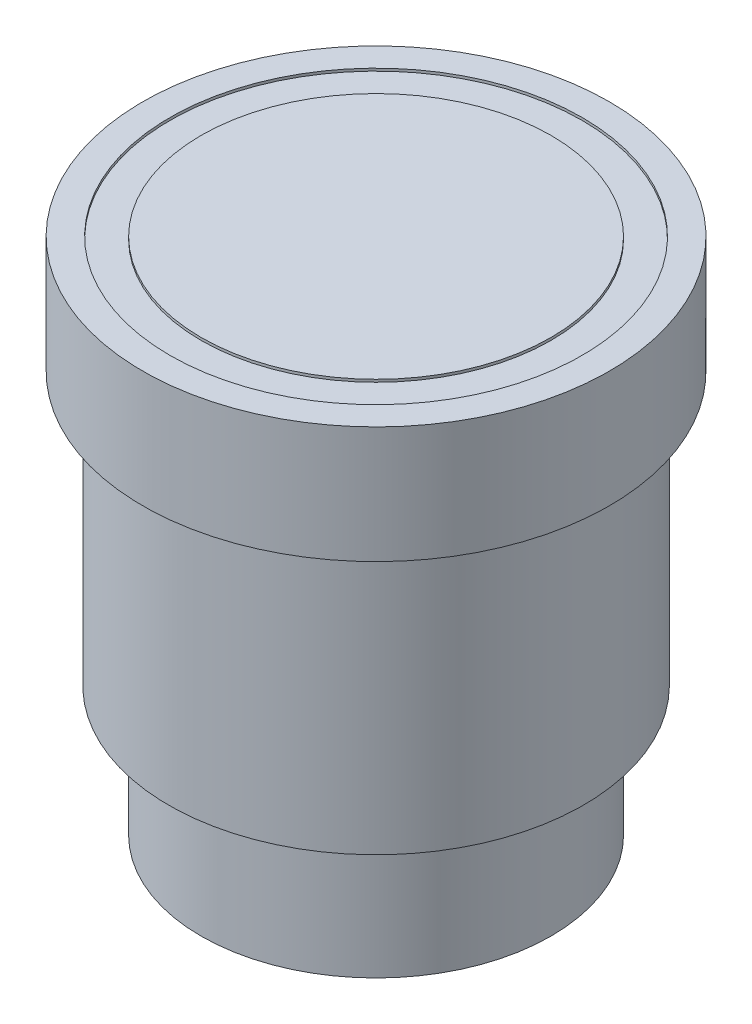
SolidWorks part; units mm, degrees
ref_plane "Front Plane" through (0, 0, 0) normal (0, 0, 1) x (1, 0, 0)
ref_plane "Top Plane" through (0, 0, 0) normal (0, 1, 0) x (1, 0, 0)
ref_plane "Right Plane" through (0, 0, 0) normal (1, 0, 0) x (0, 0, -1)
sketch "Sketch1" plane through (0, 0, 0) normal (1, 0, 0) x (0, 0, -1)
  line L0 (0, 0) -> (0, 50000) construction
  line L1 (0, 20) -> (9, 20)
  line L2 (9, 20) -> (9, 15.5)
  line L3 (9, 15.5) -> (8, 15.5)
  line L4 (8, 15.5) -> (8, 5)
  line L5 (8, 5) -> (6.75, 5)
  line L6 (6.75, 5) -> (6.75, 0)
  line L7 (6.75, 0) -> (0, 0)
  line L8 (0, 20) -> (0, 0)
  dimension "D1" = 20
  dimension "D2" = 4.5
  dimension "D3" = 18
  dimension "D4" = 16
  dimension "D5" = 5
  dimension "D6" = 13.5
revolve "Revolve1" add sketch "Sketch1" angle 360 about L0
sketch "Sketch2" plane through (0, 20, 0) normal (0, 1, 0) x (1, 0, 0)
  circle A0 centre (0, 0) radius 6.75
  circle A1 centre (0, 0) radius 7.95
  dimension "D1" = 13.5
  dimension "D2" = 1.2
extrude "Cut-Extrude1" cut sketch "Sketch2" against normal blind 0.1
